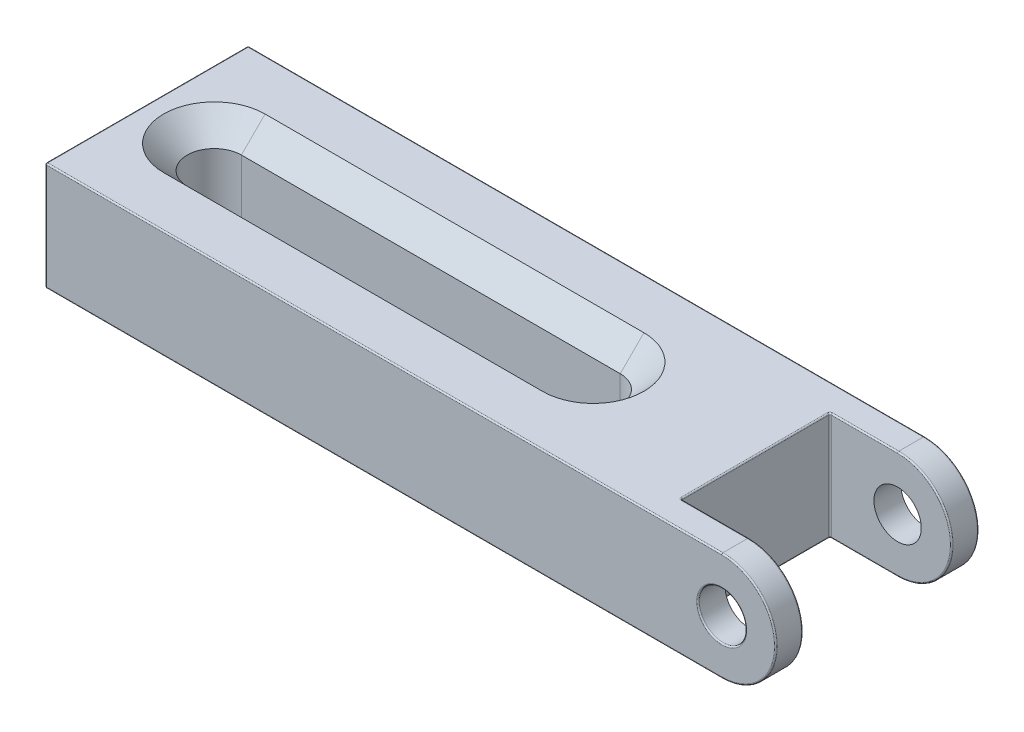
SolidWorks part; units mm, degrees
other "Markup1"
sketch "Sketch4" plane through (0, 4, 7.5) normal (-0.3483, 0.9366, 0.0377) x (0.634, 0.2058, 0.7454)
ref_plane "Front Plane" through (0, 0, 0) normal (0, 0, 1) x (1, 0, 0)
ref_plane "Top Plane" through (0, 0, 0) normal (0, 1, 0) x (1, 0, 0)
ref_plane "Right Plane" through (0, 0, 0) normal (1, 0, 0) x (0, 0, -1)
sketch "Sketch1" plane through (0, 0, 0) normal (0, 0, 1) x (1, 0, 0)
  line L0 (0, 0) -> (50, 0) construction
  line L1 (0, 4) -> (50, 4)
  line L2 (0, -4) -> (50, -4)
  line L3 (0, 4) -> (0, -4)
  arc A1 (50, -4) -> (50, 4) centre (50, 0) ccw
  circle A2 centre (50, 0) radius 1.75
  point P2 (0, 0)
  dimension "D2" = 3.5
  dimension "D1" = 8
  dimension "D3" = 50
extrude "Boss-Extrude1" add sketch "Sketch1" along normal mid plane 15
sketch "Sketch2" plane through (0, 4, 0) normal (0, 1, 0) x (1, 0, 0)
  line L0 (54, -7.5) -> (54, 7.5) construction
  line L1 (45, -5.5) -> (54, -5.5)
  line L2 (45, -5.5) -> (45, 5.5)
  line L3 (45, 5.5) -> (54, 5.5)
  line L4 (54, -5.5) -> (54, 5.5)
  line L5 (45, -5.5) -> (54, 5.5) construction
  line L6 (45, 5.5) -> (54, -5.5) construction
  line L7 (50, -7.5) -> (50, 7.5) construction
  point P0 (49.5, 0)
  dimension "D1" = 11
  dimension "D2" = 5
extrude "Cut-Extrude1" cut sketch "Sketch2" against normal through all
sketch "Sketch3" plane through (0, 4, 0) normal (0, 1, 0) x (1, 0, 0)
  line L1 (5, 0) -> (33, 0) construction
  line L2 (5, 2) -> (33, 2)
  line L3 (0, -7.5) -> (0, 7.5) construction
  line L4 (5, -2) -> (33, -2)
  line L5 (45, 5.5) -> (45, -5.5) construction
  arc A2 (5, 2) -> (5, -2) centre (5, 0) ccw
  arc A3 (33, -2) -> (33, 2) centre (33, 0) ccw
  point P2 (19, 0)
  dimension "D1" = 5
  dimension "D3" = 2
  dimension "D2" = 12
extrude "Cut-Extrude2" cut sketch "Sketch3" against normal through all
fillet "Fillet1" radius 0.1 25 edges at (45, -4, 0) (47.5, -4, -5.5) (54, 0, -5.5) (47.5, -4, 5.5) (54, 0, 5.5) (25, -4, -7.5) (54, 0, -7.5) (0, -4, 0) (0, 0, -7.5) (0, 4, 0) (25, 4, -7.5) (47.5, 4, -5.5) (45, 4, 0) (47.5, 4, 5.5) (51.75, 0, 7.5) (25, 4, 7.5) (54, 0, 7.5) (25, -4, 7.5) (0, 0, 7.5) (45, 0, 5.5) (45, 0, -5.5) (35, -4, 0) (19, -4, 2) (3, -4, 0) (19, -4, -2)
chamfer "Chamfer1" distance 1.75 angle 45 4 edges at (3, 4, 0) (19, 4, 2) (19, 4, -2) (35, 4, 0)
